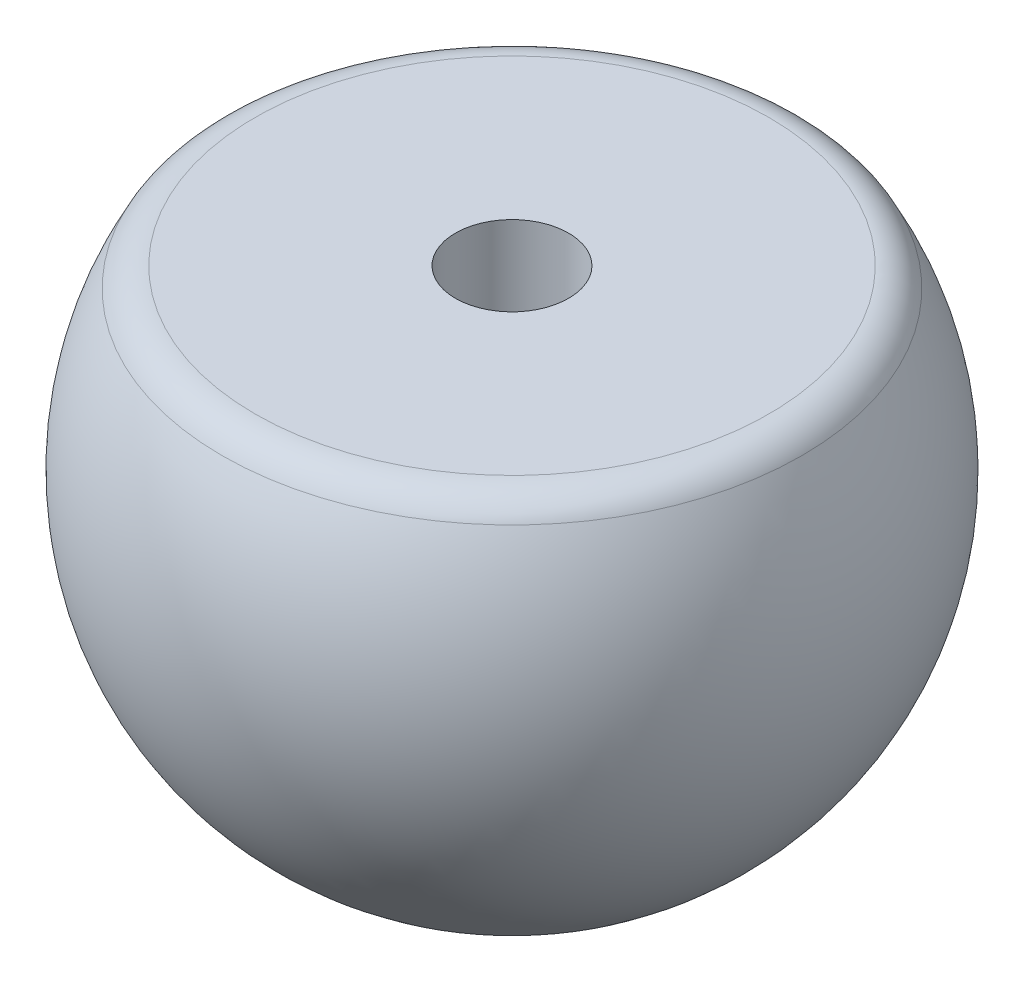
SolidWorks part; units mm, degrees
ref_plane "前视基准面" through (0, 0, 0) normal (0, 0, 1) x (1, 0, 0)
ref_plane "上视基准面" through (0, 0, 0) normal (0, 1, 0) x (1, 0, 0)
ref_plane "右视基准面" through (0, 0, 0) normal (1, 0, 0) x (0, 0, -1)
sketch "草图1" plane through (0, 0, 0) normal (0, 0, 1) x (1, 0, 0)
  line L0 (-1.2223, 5.2266) -> (-1.2223, 2.7266) construction
  line L1 (-1.2223, -6.0734) -> (-1.2223, 7.4416)
  line L2 (-1.2223, 7.4416) -> (-8.6525, 7.4416)
  circle A0 centre (-1.2223, 2.7266) radius 8.8 construction
  arc A2 (-8.6525, 7.4416) -> (-1.2223, -6.0734) centre (-1.2223, 2.7266) ccw
  dimension "D1" = 17.6
revolve "旋转1" add sketch "草图1" angle 360 about L0
sketch "草图2" plane through (0, 7.4416, 0) normal (0, 1, 0) x (1, 0, 0)
  circle A0 centre (-1.2223, 0) radius 1.51
  dimension "D1" = 3.02
extrude "切除-拉伸1" cut sketch "草图2" against normal through all both and the other way through all
ref_plane "基准面1" through (0, -10, 0) normal (0, 1, 0) x (1, 0, 0)
sketch "草图4" plane through (0, -10, 0) normal (0, 1, 0) x (1, 0, 0)
  circle A0 centre (-1.2223, 0) radius 4.6437
extrude "切除-拉伸2" cut sketch "草图4" along normal blind 5
sketch "草图5" plane through (0, -5, 0) normal (0, -1, 0) x (1, 0, 0)
  circle A0 centre (-1.2223, 0) radius 3.6769
extrude "切除-拉伸3" cut sketch "草图5" against normal blind 3
fillet "圆角1" radius 1 1 edges at (-1.2223, 7.4416, 7.4303)
